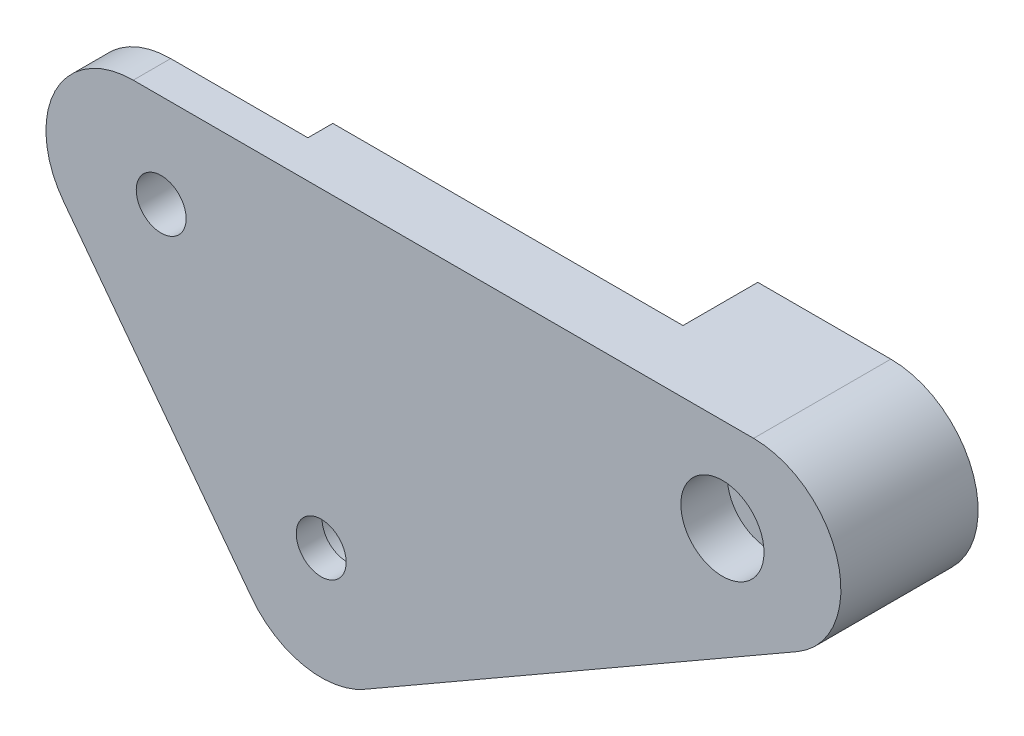
SolidWorks part; units mm, degrees
ref_plane "前视基准面" through (0, 0, 0) normal (0, 0, 1) x (1, 0, 0)
ref_plane "上视基准面" through (0, 0, 0) normal (0, 1, 0) x (1, 0, 0)
ref_plane "右视基准面" through (0, 0, 0) normal (1, 0, 0) x (0, 0, -1)
other "Configuration Table"
sketch "草图1" plane through (0, 0, 0) normal (0, 0, 1) x (1, 0, 0)
  line L0 (14.0598, 0) -> (63.7983, 0)
  line L1 (67.2893, -13.0673) -> (32.6188, -33.0162)
  line L2 (23.5421, -31.1679) -> (8.4741, -11.219)
  arc A0 (14.0598, 0) -> (8.4741, -11.219) centre (14.0598, -7) ccw
  arc A1 (32.6188, -33.0162) -> (23.5421, -31.1679) centre (29.1278, -26.9488) cw
  arc A2 (63.7983, 0) -> (67.2893, -13.0673) centre (63.7983, -7) cw
  circle A6 centre (29.1278, -24.9488) radius 3.3333
  circle A7 centre (15.5598, -7.5) radius 5
  circle A8 centre (61.2983, -7.5) radius 5
  point P6 (0, 0)
  point P11 (90, 0)
  dimension "D2" = 7
  dimension "D3" = 40
  dimension "D5" = 10
  dimension "D6" = 10
  dimension "D7" = 6.6667
  dimension "D1" = 90
  dimension "D4" = 25
  dimension "D8" = 2
  dimension "D9" = 7.5
  dimension "D10" = 2.5
  dimension "D11" = 1.5
extrude "凸台-拉伸1" add sketch "草图1" along normal blind 5
sketch "草图6" plane through (0, 0, 0) normal (0, 0, -1) x (-1, 0, 0)
  line L0 (-67.2893, -13.0673) -> (-32.6188, -33.0162) construction
  line L1 (-55.1112, -20.0745) -> (-49.187, -12.7831)
  line L2 (-49.187, -12.7831) -> (-53.1341, 0)
  line L3 (-14.0598, 0) -> (-63.7983, 0) construction
  line L4 (-53.1341, 0) -> (-63.7983, 0)
  line L5 (-67.2893, -13.0673) -> (-55.1112, -20.0745)
  arc A0 (-63.7983, 0) -> (-67.2893, -13.0673) centre (-63.7983, -7) ccw
  circle A1 centre (-61.2983, -7.5) radius 3
  circle M2 centre (-61.2983, -7.5) radius 5
  arc M4 (-63.7983, 0) -> (-67.2893, -13.0673) centre (-63.7983, -7) ccw
  line M9 (-14.0598, 0) -> (-63.7983, 0)
  dimension "D1" = 6
extrude "凸台-拉伸5" add sketch "草图6" along normal blind 6 contours L5 L1 L2 M4 M9 M2
sketch "草图7" plane through (0, 0, 0) normal (0, 0, -1) x (-1, 0, 0)
  line L0 (-14.0598, 0) -> (-53.1341, 0) construction
  line L1 (-25.0598, 0) -> (-26.1639, -10)
  line L2 (-26.1639, -10) -> (-13.0401, -17.264)
  line L3 (-23.5421, -31.1679) -> (-8.4741, -11.219) construction
  line L9 (-53.1341, 0) -> (-49.187, -12.7831)
  line L10 (-49.187, -12.7831) -> (-55.1112, -20.0745)
  line L11 (-55.1112, -20.0745) -> (-32.6188, -33.0162)
  line L12 (-23.5421, -31.1679) -> (-8.4741, -11.219)
  line L13 (-14.0598, 0) -> (-53.1341, 0)
  line L14 (-53.1341, 0) -> (-49.187, -12.7831)
  line L15 (-49.187, -12.7831) -> (-55.1112, -20.0745)
  line L16 (-55.1112, -20.0745) -> (-32.6188, -33.0162)
  line L17 (-23.5421, -31.1679) -> (-8.4741, -11.219)
  line L18 (-14.0598, 0) -> (-53.1341, 0)
  circle A0 centre (-16.2983, -7.5) radius 2
  circle A1 centre (-61.2983, -7.5) radius 5 construction
  arc A4 (-32.6188, -33.0162) -> (-23.5421, -31.1679) centre (-29.1278, -26.9488) ccw
  arc A5 (-8.4741, -11.219) -> (-14.0598, 0) centre (-14.0598, -7) ccw
  arc A6 (-32.6188, -33.0162) -> (-23.5421, -31.1679) centre (-29.1278, -26.9488) ccw
  arc A7 (-8.4741, -11.219) -> (-14.0598, 0) centre (-14.0598, -7) ccw
  line M16 (-23.5421, -31.1679) -> (-8.4741, -11.219)
  arc M17 (-8.4741, -11.219) -> (-14.0598, 0) centre (-14.0598, -7) ccw
  line M18 (-14.0598, 0) -> (-53.1341, 0)
  dimension "D1" = 4
  dimension "D2" = 45
  dimension "D3" = 7.5
  dimension "D4" = 0
  dimension "D5" = 11
  dimension "D6" = 10
  dimension "D7" = 15
  dimension "D8" = 7.5
extrude "凸台-拉伸6" add sketch "草图7" along normal blind 2 contours L1 L2 A0 M16 M17 M18
sketch "草图9" plane through (0, 0, 0) normal (0, 0, -1) x (-1, 0, 0)
  circle A1 centre (-16.2983, -7.5) radius 2
  circle A3 centre (-16.2983, -7.5) radius 2
  dimension "D1" = 0
extrude "切除-拉伸3" cut sketch "草图9" against normal through all
sketch "草图10" plane through (0, 0, 5) normal (0, 0, 1) x (1, 0, 0)
  circle A0 centre (61.2983, -7.5) radius 5 construction
  circle A1 centre (61.2983, -7.5) radius 5
  circle A2 centre (61.2983, -7.5) radius 2
  dimension "D1" = 4
extrude "凸台-拉伸7" add sketch "草图10" against normal up to surface (11 mm away) up to face at (56.2983, -7.5, -6)
fillet "圆角2" radius 10 2 edges at (26.1639, -10, -1) (49.187, -12.7831, -3)
scale "缩放比例1" scale about centroid uniform scaling yes scale factor 1.5
sketch "草图11" plane through (0, 0, -3.6477) normal (0, 0, -1) x (-1, 0, 0)
  line L0 (-15.0698, -40.9306) -> (0.6832, -20.0748) construction
  line L4 (-17.3463, 5.8212) -> (-17.906, 0.7525)
  line L5 (-10.2606, -14.0175) -> (0.6832, -20.0748)
  line L6 (0.6832, -20.0748) -> (7.5322, -11.0074)
  line L7 (-0.8463, 5.8212) -> (-17.3463, 5.8212)
  line L8 (-17.3463, 5.8212) -> (-17.906, 0.7525)
  line L10 (-4.8596, -27.4132) -> (7.5322, -11.0074)
  line L11 (-0.8463, 5.8212) -> (-17.3463, 5.8212)
  circle A0 centre (-4.2041, -5.4288) radius 3 construction
  circle A1 centre (-4.2041, -5.4288) radius 3
  arc A2 (-17.906, 0.7525) -> (-10.2606, -14.0175) centre (-2.9966, -0.8937) ccw
  arc A3 (7.5322, -11.0074) -> (-0.8463, 5.8212) centre (-0.8463, -4.6788) ccw
  arc A5 (7.5322, -11.0074) -> (-0.8463, 5.8212) centre (-0.8463, -4.6788) ccw
  arc A6 (-17.906, 0.7525) -> (-4.8596, -27.4132) centre (11.9128, -2.5398) ccw
  dimension "D2" = 30
  dimension "D1" = 0
extrude "切除-拉伸4" cut sketch "草图11" against normal blind 6
sketch "草图12" plane through (0, 0, 6.8523) normal (0, 0, 1) x (1, 0, 0)
  circle A0 centre (71.7041, -5.4288) radius 2.6
  circle A1 centre (71.7041, -5.4288) radius 3
  dimension "D1" = 5.2
extrude "凸台-拉伸8" add sketch "草图12" against normal blind 15
sketch "草图13" plane through (0, 0, 6.8523) normal (0, 0, 1) x (1, 0, 0)
  circle A0 centre (71.7041, -5.4288) radius 5
  dimension "D1" = 10
extrude "切除-拉伸5" cut sketch "草图13" against normal blind 5.6
sketch "草图15" plane through (0, 0, -0.6477) normal (0, 0, -1) x (-1, 0, 0)
  circle A0 centre (-23.4483, -31.6021) radius 5
  circle A1 centre (-23.4483, -31.6021) radius 3
  dimension "D1" = 6
  dimension "D2" = 10
extrude "凸台-拉伸9" add sketch "草图15" against normal up to surface (3.1 mm away) from offset 4.4 up to face at (76.7041, -5.4288, 6.8523) offset against normal yes
sketch "草图16" plane through (0, 0, -0.6477) normal (0, 0, -1) x (-1, 0, 0)
  circle A0 centre (-23.4483, -31.6021) radius 6
  dimension "D1" = 12
extrude "切除-拉伸6" cut sketch "草图16" against normal blind 0.4
